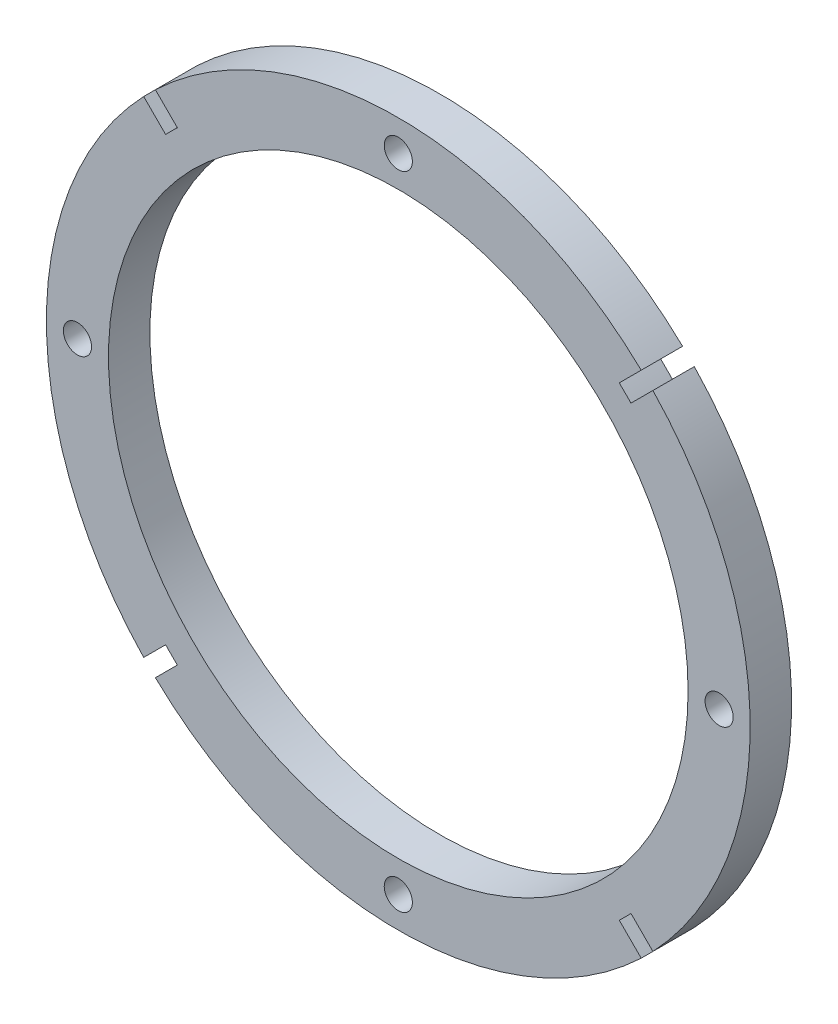
SolidWorks part; units mm, degrees
material "6063-T6"
ref_plane "Płaszczyzna przednia" through (0, 0, 0) normal (0, 0, 1) x (1, 0, 0)
ref_plane "Płaszczyzna górna" through (0, 0, 0) normal (0, 1, 0) x (1, 0, 0)
ref_plane "Płaszczyzna prawa" through (0, 0, 0) normal (1, 0, 0) x (0, 0, -1)
sketch "Szkic1" plane through (0, 0, 0) normal (0, 0, 1) x (1, 0, 0)
  circle A0 centre (0, 0) radius 85
  circle A1 centre (0, 0) radius 70
  dimension "D1" = 140
  dimension "D2" = 170
extrude "Dodanie-wyciągnięcie1" add sketch "Szkic1" along normal blind 10 contours A1 | A0
sketch "Szkic2" plane through (0, 0, 10) normal (0, 0, 1) x (1, 0, 0)
  line L0 (0, 92.4389) -> (0, -92.4389) construction
  line L1 (0, 0) -> (-73.1252, 73.1252) construction
  line L3 (-56.1967, 53.3683) -> (-61.5016, 58.6732)
  line L4 (-53.3683, 56.1967) -> (-58.6732, 61.5016)
  line L6 (-1.4142, -1.4142) -> (-74.5394, 71.711) construction
  circle A0 centre (0, 77.5) radius 3.4
  circle A1 centre (0, 0) radius 70 construction
  arc A5 (-58.6732, 61.5016) -> (-61.5016, 58.6732) centre (0, 0) ccw
  arc A6 (-53.3683, 56.1967) -> (-56.1967, 53.3683) centre (0, 0) ccw
  point P10 (1.4142, 8.6364)
  point P11 (-71.711, 81.7616)
  dimension "D2" = 6.8
  dimension "D7" = 7.5
  dimension "D1" = 45
  dimension "D3" = 77.5
  dimension "D4" = 4
  dimension "D5" = 2
extrude "Wytnij-wyciągnięcie1" cut sketch "Szkic2" against normal blind 10
pattern_circular "Szyk kołowy1" count 4 over 360 about axis through (0, 0, 0) along (0, 0, 1) of "Wytnij-wyciągnięcie1"
